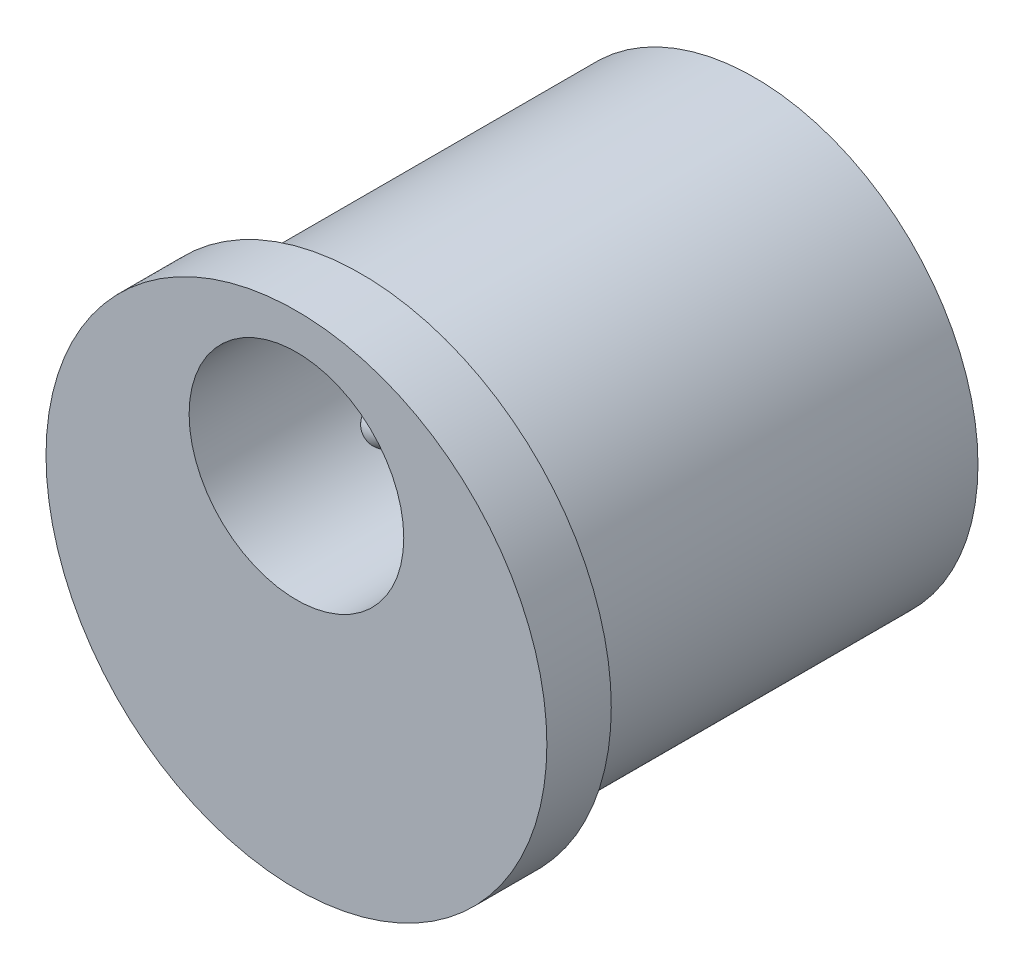
SolidWorks part; units mm, degrees
ref_plane "Plano frontal" through (0, 0, 0) normal (0, 0, 1) x (1, 0, 0)
ref_plane "Plano superior" through (0, 0, 0) normal (0, 1, 0) x (1, 0, 0)
ref_plane "Plano direito" through (0, 0, 0) normal (1, 0, 0) x (0, 0, -1)
sketch "Esboço1" plane through (0, 0, 0) normal (0, 0, 1) x (1, 0, 0)
  line L0 (0, 0) -> (0, 3) construction
  circle A0 centre (0, 0) radius 7
  circle A1 centre (0, 3) radius 3
  dimension "D1" = 14
  dimension "D3" = 6
  dimension "D2" = 3
extrude "Ressalto-extrusão1" add sketch "Esboço1" along normal blind 1.8
sketch "Esboço2" plane through (0, 0, 0) normal (0, 0, -1) x (-1, 0, 0)
  circle A0 centre (0, 0) radius 6.25
  dimension "D1" = 12.5
extrude "Ressalto-extrusão2" add sketch "Esboço2" along normal blind 11
sketch "Esboço3" plane through (0, 0, 1.8) normal (0, 0, 1) x (1, 0, 0)
  circle A0 centre (0, 3) radius 3
extrude "Corte-extrusão1" cut sketch "Esboço3" against normal blind 11
sketch "Esboço4" plane through (0, 0, -9.2) normal (0, 0, 1) x (1, 0, 0)
  circle A0 centre (0, 3) radius 0.5
  dimension "D1" = 1
extrude "Ressalto-extrusão3" add sketch "Esboço4" along normal blind 9
fillet "Filete1" radius 0.5 1 edges at (0.5, 3, -0.2)
sketch "Esboço5" plane through (0, 0, -11) normal (0, 0, -1) x (-1, 0, 0)
  line L1 (-1.9048, -5.3453) -> (2.0952, -5.3453)
  line L2 (-1.9048, -5.3453) -> (-1.9048, -5.0795)
  line L3 (-1.9048, -5.0795) -> (2.0952, -5.0795)
  line L4 (2.0952, -5.3453) -> (2.0952, -5.0795)
  line L5 (5.1863, -2.002) -> (5.393, -2.002)
  line L6 (5.1863, -2.002) -> (5.1863, 1.998)
  line L7 (5.1863, 1.998) -> (5.393, 1.998)
  line L8 (5.393, -2.002) -> (5.393, 1.998)
  dimension "D1" = 4
  dimension "D2" = 4
extrude "Ressalto-extrusão4" add sketch "Esboço5" along normal blind 4.5
sketch "Esboço6" plane through (-5.393, 0, 0) normal (-1, 0, 0) x (0, 0, 1)
  line L1 (-14, -2.002) -> (-11, -2.002)
  line L2 (-15.5, -0.502) -> (-15.5, 0.498)
  line L3 (-14, 1.998) -> (-11, 1.998)
  line L4 (-11, -2.002) -> (-11, 1.998)
  arc A0 (-14, -2.002) -> (-15.5, -0.502) centre (-14, -0.502) cw
  arc A1 (-15.5, 0.498) -> (-14, 1.998) centre (-14, 0.498) cw
  point P8 (-15.5, -2.002)
  line M8 (-11, 1.998) -> (-15.5, 1.998)
  line M9 (-15.5, 1.998) -> (-15.5, -2.002)
  line M10 (-15.5, -2.002) -> (-11, -2.002)
  dimension "D1" = 1.5
extrude "Corte-extrusão2" cut sketch "Esboço6" against normal mid plane 4.5 contours A0 M10 M9 | A1 M9 M8
sketch "Esboço7" plane through (0, -5.3453, 0) normal (0, -1, 0) x (1, 0, 0)
  line L0 (1.9048, -14) -> (1.9048, -15.5)
  line L1 (0.4048, -15.5) -> (-0.5952, -15.5)
  line L2 (1.9048, -14) -> (1.9048, -11)
  line L3 (1.9048, -11) -> (-2.0952, -11)
  line L4 (-2.0952, -14) -> (-2.0952, -11)
  line L5 (1.9048, -15.5) -> (-2.0952, -15.5)
  line L6 (-2.0952, -15.5) -> (-2.0952, -14)
  arc A0 (-0.5952, -15.5) -> (-2.0952, -14) centre (-0.5952, -14) cw
  arc A1 (0.4048, -15.5) -> (1.9048, -14) centre (0.4048, -14) ccw
  point P10 (1.9048, -15.5)
  line M8 (-2.0952, -11) -> (-2.0952, -15.5)
  line M9 (-2.0952, -15.5) -> (1.9048, -15.5)
  line M10 (1.9048, -15.5) -> (1.9048, -11)
  dimension "D1" = 1.5
extrude "Corte-extrusão3" cut sketch "Esboço7" against normal mid plane 4.5 contours A1 M9 M10 | A0 M9 M8
